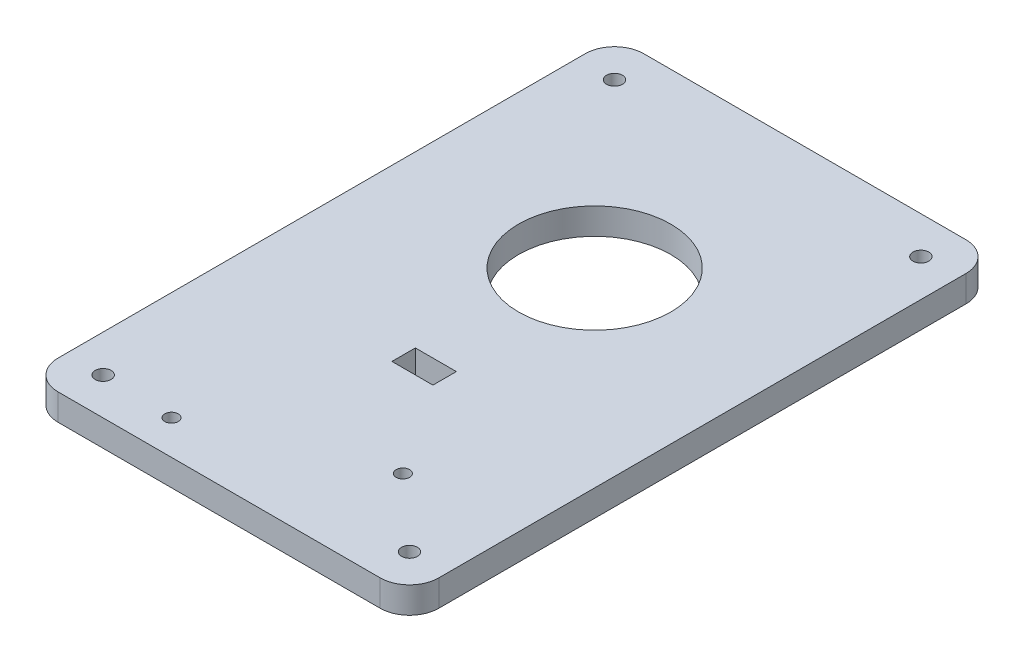
SolidWorks part; units mm, degrees
ref_plane "Front Plane" through (0, 0, 0) normal (0, 0, 1) x (1, 0, 0)
ref_plane "Top Plane" through (0, 0, 0) normal (0, 1, 0) x (1, 0, 0)
ref_plane "Right Plane" through (0, 0, 0) normal (1, 0, 0) x (0, 0, -1)
sketch "Sketch2" plane through (0, 0, 0) normal (0, 1, 0) x (1, 0, 0)
  line L1 (-32.5, 50) -> (32.5, 50)
  line L2 (-32.5, 50) -> (-32.5, -50)
  line L3 (-32.5, -50) -> (32.5, -50)
  line L4 (32.5, 50) -> (32.5, -50)
  line L5 (-32.5, 50) -> (32.5, -50) construction
  line L6 (-32.5, -50) -> (32.5, 50) construction
  point P0 (0, 0)
  dimension "D1" = 65
  dimension "D2" = 100
extrude "Boss-Extrude1" add sketch "Sketch2" along normal blind 4.5
sketch "Sketch3" plane through (0, 4.5, 0) normal (0, 1, 0) x (1, 0, 0)
  line L0 (-32.5, 50) -> (-32.5, -50) construction
  line L1 (32.5, 50) -> (-32.5, 50) construction
  line L2 (32.5, -50) -> (32.5, 50) construction
  line L3 (-32.5, -50) -> (32.5, -50) construction
  point P0 (-26.15, 43.65)
  point P1 (26.15, 43.65)
  point P2 (26.15, -43.65)
  point P3 (-26.15, -43.65)
  dimension "D1" = 6.35
  dimension "D2" = 6.35
  dimension "D3" = 6.35
  dimension "D4" = 6.35
hole_wizard "#36 (0.1065) Diameter Hole1" positions "Sketch4" profile "Sketch5" hole size "#36" standard "ANSI Inch" end condition through all
sketch "Sketch4" plane through (0, 4.5, 0) normal (0, 1, 0) x (1, 0, 0)
  point P0 (-26.15, 43.65)
  point P3 (26.15, 43.65)
  point P6 (26.15, -43.65)
  point P9 (-26.15, -43.65)
sketch "Sketch5" plane through (-26.15, 4.5, -43.65) normal (1, 0, 0) x (0, 0, 1)
  line L0 (0, 0) -> (0, 4.5)
  line L1 (0, 4.5) -> (1.3525, 4.5)
  line L2 (1.3525, 4.5) -> (1.3525, 0)
  line L5 (1.3525, 0) -> (0, 0)
  line L11 (0, -6.35) -> (0, 107.95) construction
  dimension "Thru Hole Dia." = 2.7051
  dimension "Thru Hole Depth" = 4.5
fillet "Fillet1" radius 5 4 edges at (-32.5, 2.25, -50) (32.5, 2.25, -50) (32.5, 2.25, 50) (-32.5, 2.25, 50)
sketch "Sketch10" plane through (0, 4.5, 5) normal (0, 1, 0) x (1, 0, 0)
  line L1 (-14, -27.6314) -> (14, -27.6314)
  line L2 (-14, -27.6314) -> (-14, -39.1314)
  line L3 (-14, -39.1314) -> (14, -39.1314)
  line L4 (14, -27.6314) -> (14, -39.1314)
  line L5 (-14, -27.6314) -> (14, -39.1314) construction
  line L6 (-14, -39.1314) -> (14, -27.6314) construction
  point P0 (0, 0)
  point P1 (0, -33.3814)
  point P3 (0, -33.3814)
  dimension "D1" = 28
  dimension "D2" = 11.5
sketch "Sketch11" plane through (0, 4.5, 0) normal (0, 1, 0) x (1, 0, 0)
  point P0 (14, -32.6314)
  point P1 (-14, -44.1314)
hole_wizard "Tap Drill for M2.2 Helicoil1" positions "Sketch12" profile "Sketch13" hole size "M2.2x0.45" standard "ANSI Metric"
sketch "Sketch12" plane through (0, 4.5, 0) normal (0, 1, 0) x (1, 0, 0)
  point P0 (14, -32.6314)
  point P3 (-14, -44.1314)
sketch "Sketch13" plane through (14, 4.5, 32.6314) normal (1, 0, 0) x (0, 0, 1)
  line L0 (0, 0) -> (0, 5.191)
  line L1 (0, 5.191) -> (1.15, 4.5)
  line L2 (1.15, 4.5) -> (1.15, 0)
  line L5 (1.15, 0) -> (0, 0)
  line L10 (0, 5.191) -> (-1.15, 4.5) construction
  line L11 (0, -6.35) -> (0, 107.95) construction
  dimension "Hole Dia." = 2.3
  dimension "Hole Depth" = 4.5
  dimension "Drill Angle" = 118
sketch "Sketch14" plane through (0, 4.5, 0) normal (0, 1, 0) x (1, 0, 0)
  line L1 (-3.5, -13) -> (3.5, -13)
  line L2 (-3.5, -13) -> (-3.5, -17)
  line L3 (-3.5, -17) -> (3.5, -17)
  line L4 (3.5, -13) -> (3.5, -17)
  line L5 (-3.5, -13) -> (3.5, -17) construction
  line L6 (-3.5, -17) -> (3.5, -13) construction
  point P0 (0, -15)
  point P8 (0, -13)
  dimension "D1" = 4
  dimension "D2" = 7
  dimension "D3" = 10
extrude "Cut-Extrude1" cut sketch "Sketch14" against normal blind 10
sketch "Sketch16" plane through (0, 4.5, 0) normal (0, 1, 0) x (1, 0, 0)
  circle A0 centre (0, 14.1154) radius 13
  dimension "D1" = 26
extrude "Cut-Extrude2" cut sketch "Sketch16" against normal blind 17
